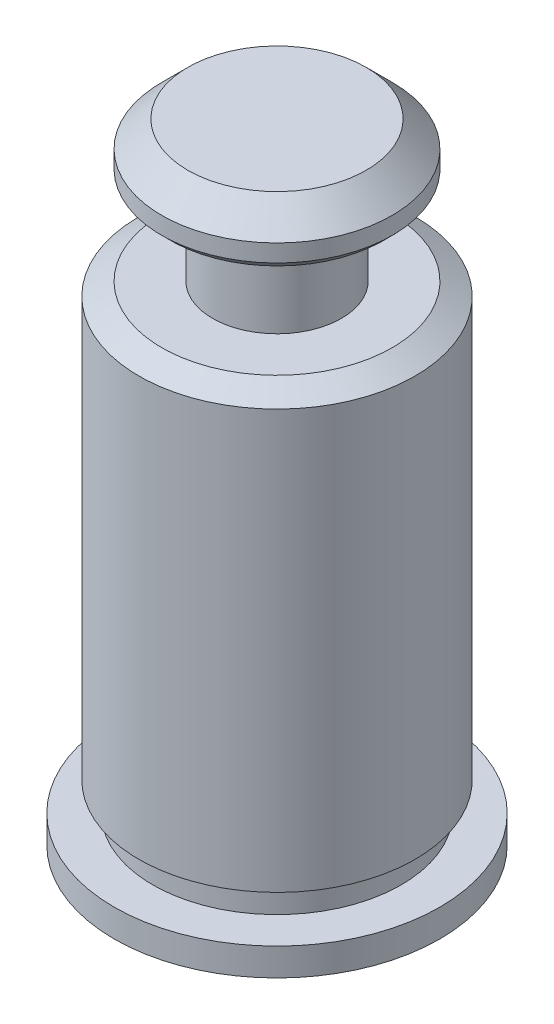
SolidWorks part; units mm, degrees
ref_plane "Plane1" through (0, 0, 0) normal (0, 0, 1) x (1, 0, 0)
ref_plane "Plane2" through (0, 0, 0) normal (0, 1, 0) x (1, 0, 0)
ref_plane "Plane3" through (0, 0, 0) normal (1, 0, 0) x (0, 0, -1)
sketch "BodySke" plane through (0, 0, 0) normal (0, 0, 1) x (1, 0, 0)
  line L0 (2.6924, 0) -> (3.175, 0)
  line L1 (3.175, 0) -> (3.175, 0.5385)
  line L2 (3.175, 0.5385) -> (2.4232, 0.5385)
  line L3 (1.2573, 9.525) -> (1.2573, 11.2522)
  line L4 (2.6924, 1.1039) -> (2.4232, 1.1039)
  line L5 (2.4232, 1.1039) -> (2.4232, 0.5385)
  line L6 (2.6924, 0.0051) -> (2.6924, 0)
  line L7 (0, 0.0051) -> (2.6924, 0.0051)
  line L8 (2.2479, 9.525) -> (1.2573, 9.525)
  line L9 (0, 0) -> (0, 15.24) construction
  line L10 (1.2573, 11.2522) -> (2.0786, 11.2522)
  line L11 (2.6924, 9.2684) -> (2.6924, 1.1039)
  line L12 (2.0786, 11.2522) -> (2.2479, 11.4215)
  line L13 (0, 0.0051) -> (0, 12.2682)
  line L14 (2.2479, 11.4215) -> (2.2479, 11.7602)
  line L15 (2.2479, 11.7602) -> (1.7399, 12.2682)
  line L16 (1.7399, 12.2682) -> (0, 12.2682)
  line L17 (2.2479, 9.525) -> (2.6924, 9.2684)
  dimension "H_dia" = 6.35
  dimension "C_dia" = 5.3848
  dimension "Length" = 9.525
  dimension "Clinching_ht" = 0.5385
  dimension "Groove_wid" = 0.5654
  dimension "Groove_dia" = 4.8463
  dimension "D1" = 0.0051
  dimension "B_dia" = 4.4958
  dimension "A_dia" = 2.5146
  dimension "S_dim" = 1.7272
  dimension "M_dim" = 2.7432
  dimension "D2" = 45
  dimension "Top_chamfer_ht" = 0.508
  dimension "D3" = 45
  dimension "Under_chamfer_ht" = 0.1693
  dimension "D4" = 30
revolve "Body" add sketch "BodySke" angle 360 about L9
ref_plane "Plane4" through (0, -0.5486, 0) normal (0, 1, 0) x (-1, 0, 0)
equation "' \"Length@BodySke\" = 0.375"
equation "' \"A_dia@BodySke\" = 0.099"
equation "' \"B_dia@BodySke\" = 0.177"
equation "' \"C_dia@BodySke\" = 0.212"
equation "' \"S_dim@BodySke\" = 0.068"
equation "' \"M_dim@BodySke\" = 0.108"
equation "' \"H_dia@BodySke\" = 0.25"
equation "\"Top_chamfer_ht@BodySke\" = ( \"M_dim@BodySke\" - \"S_dim@BodySke\" ) * 0.5"
equation "\"Under_chamfer_ht@BodySke\" = \"Top_chamfer_ht@BodySke\" / 3"
equation "\"Clinching_ht@BodySke\" = \"C_dia@BodySke\" * 0.1"
equation "\"Groove_dia@BodySke\" = \"C_dia@BodySke\" * 0.9"
equation "\"Groove_wid@BodySke\" = \"Clinching_ht@BodySke\" * 1.05"
